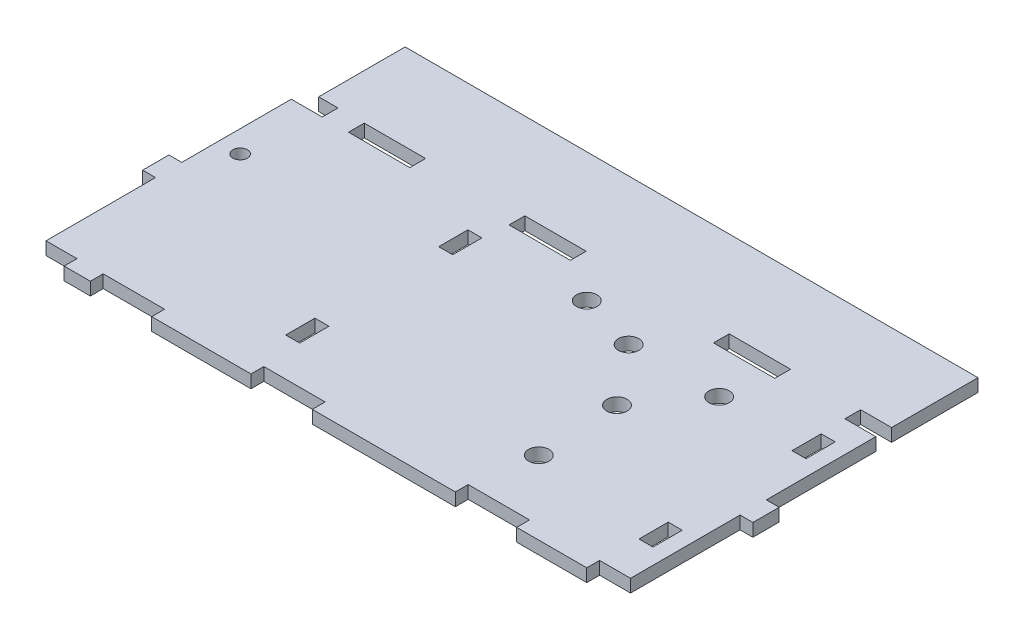
SolidWorks part; units mm, degrees
ref_plane "Front Plane" through (0, 0, 0) normal (0, 0, 1) x (1, 0, 0)
ref_plane "Top Plane" through (0, 0, 0) normal (0, 1, 0) x (1, 0, 0)
ref_plane "Right Plane" through (0, 0, 0) normal (1, 0, 0) x (0, 0, -1)
sketch "Sketch1" plane through (0, 0, 0) normal (0, 1, 0) x (1, 0, 0)
  line L0 (-110.6901, 12.3801) -> (-116.2781, 12.3801)
  line L2 (-110.6901, -46.6749) -> (-110.6901, 0.9501)
  line L4 (143.5639, -46.6749) -> (143.5639, 0.9501)
  line L5 (-110.6901, -46.6749) -> (143.5639, 60.0051) construction
  line L6 (-110.6901, 60.0051) -> (143.5639, -46.6749) construction
  line L7 (-116.2781, 12.3801) -> (-116.2781, 0.9501)
  line L8 (-116.2781, 0.9501) -> (-110.6901, 0.9501)
  line L9 (-110.6901, 12.3801) -> (-110.6901, 60.0051)
  line L10 (10.7219, 63.4341) -> (72.9519, 63.4341) construction
  line L11 (149.1519, 0.9501) -> (143.5639, 0.9501)
  line L12 (149.1519, 12.3801) -> (149.1519, 0.9501)
  line L13 (143.5639, 12.3801) -> (149.1519, 12.3801)
  line L14 (143.5639, 12.3801) -> (143.5639, 60.0051)
  line L23 (-108.712, 0) -> (106.818, 0) construction
  line L32 (-110.6901, 60.0051) -> (-97.2281, 60.0051)
  line L33 (-110.6901, -46.6749) -> (-97.2281, -46.6749)
  line L34 (-85.7981, 60.0051) -> (-59.1281, 60.0051)
  line L36 (-97.2281, 60.0051) -> (-97.2281, 66.8631)
  line L38 (-85.7981, 60.0051) -> (-85.7981, 66.8631)
  line L40 (-59.1281, 60.0051) -> (-59.1281, 66.8631)
  line L42 (-15.9481, 60.0051) -> (-15.9481, 66.8631)
  line L44 (10.7219, 60.0051) -> (10.7219, 66.8631)
  line L46 (72.9519, 60.0051) -> (72.9519, 66.8631)
  line L48 (99.6219, 60.0051) -> (99.6219, 66.8631)
  line L50 (130.1019, 60.0051) -> (130.1019, 66.8631)
  line L51 (-15.9481, 60.0051) -> (10.7219, 60.0051)
  line L52 (72.9519, 60.0051) -> (99.6219, 60.0051)
  line L53 (130.1019, 60.0051) -> (143.5639, 60.0051)
  line L54 (130.1019, -46.6749) -> (130.1019, -52.2629)
  line L55 (99.6219, -52.2629) -> (130.1019, -52.2629)
  line L56 (99.6219, -46.6749) -> (99.6219, -52.2629)
  line L57 (72.9519, -46.6749) -> (72.9519, -52.2629)
  line L58 (10.7219, -52.2629) -> (72.9519, -52.2629)
  line L59 (10.7219, -46.6749) -> (10.7219, -52.2629)
  line L60 (-15.9481, -46.6749) -> (-15.9481, -52.2629)
  line L61 (-59.1281, -52.2629) -> (-15.9481, -52.2629)
  line L62 (-59.1281, -46.6749) -> (-59.1281, -52.2629)
  line L63 (-85.7981, -46.6749) -> (-85.7981, -52.2629)
  line L64 (-97.2281, -52.2629) -> (-85.7981, -52.2629)
  line L65 (-97.2281, -46.6749) -> (-97.2281, -52.2629)
  line L66 (-85.7981, -46.6749) -> (-59.1281, -46.6749)
  line L67 (-15.9481, -46.6749) -> (10.7219, -46.6749)
  line L68 (72.9519, -46.6749) -> (99.6219, -46.6749)
  line L69 (130.1019, -46.6749) -> (143.5639, -46.6749)
  line L70 (130.1019, 66.8631) -> (143.5639, 66.8631)
  line L71 (143.5639, 66.8631) -> (143.5639, 104.4551)
  line L72 (-97.2281, 66.8631) -> (-105.6101, 66.8631)
  line L73 (-105.6101, 66.8631) -> (-105.6101, 104.4551)
  line L74 (-105.6101, 104.4551) -> (143.5639, 104.4551)
  line L75 (99.6219, 66.8631) -> (72.9519, 66.8631)
  line L76 (10.7219, 66.8631) -> (-15.9481, 66.8631)
  line L77 (-59.1281, 66.8631) -> (-85.7981, 66.8631)
  line L78 (-97.2281, 63.4341) -> (-85.7981, 63.4341) construction
  line L79 (-91.5131, 63.4341) -> (-91.5131, -53.3153) construction
  line L80 (-59.1281, 63.4341) -> (-15.9481, 63.4341) construction
  line L81 (-37.5381, 63.4341) -> (-37.5381, -52.2629) construction
  line L82 (41.8369, 63.4341) -> (41.8369, -52.2629) construction
  line L83 (99.6219, 63.4341) -> (130.1019, 63.4341) construction
  line L84 (114.8619, 63.4341) -> (114.8619, -52.2629) construction
  point P0 (0, 0)
  point P57 (-91.5131, -52.2629)
  point P63 (-37.5381, -52.2629)
  point P66 (41.8369, -52.2629)
  dimension "D1" = 106.68
  dimension "D3" = 11.43
  dimension "D4" = 5.588
  dimension "D5" = 6.858
  dimension "D6" = 11.43
  dimension "D7" = 26.67
  dimension "D8" = 13.462
  dimension "D10" = 106.68
  dimension "D11" = 11.43
  dimension "D12" = 6.858
  dimension "D13" = 37.592
  dimension "D14" = 5.588
  dimension "D15" = 5.588
  dimension "D16" = 47.625
  dimension "D17" = 47.625
  dimension "D18" = 47.625
  dimension "D19" = 47.625
  dimension "D20" = 62.23
  dimension "D21" = 11.43
  dimension "D23" = 43.18
  dimension "D26" = 26.67
  dimension "D27" = 30.48
  dimension "D28" = 13.462
  dimension "D29" = 110.6901
  dimension "D30" = 26.67
  dimension "D31" = 43.18
  dimension "D32" = 62.23
  dimension "D33" = 26.67
  dimension "D34" = 30.48
  dimension "D35" = 8.382
extrude "Boss-Extrude1" add sketch "Sketch1" along normal blind 5.588
sketch "Sketch9" plane through (0, 5.588, 0) normal (0, 1, 0) x (1, 0, 0)
  line L0 (-110.6901, 0.9501) -> (-110.6901, -46.6749) construction
  line L1 (-23.0601, -17.3379) -> (-16.9641, -17.3379)
  line L2 (-23.0601, -17.3379) -> (-23.0601, -30.0379)
  line L3 (-23.0601, -30.0379) -> (-16.9641, -30.0379)
  line L4 (-16.9641, -17.3379) -> (-16.9641, -30.0379)
  line L5 (-85.7981, -46.6749) -> (-59.1281, -46.6749) construction
  line L6 (-23.0601, 36.5101) -> (-16.9641, 36.5101)
  line L7 (-23.0601, 36.5101) -> (-23.0601, 49.2101)
  line L8 (-23.0601, 49.2101) -> (-16.9641, 49.2101)
  line L9 (-16.9641, 36.5101) -> (-16.9641, 49.2101)
  line L10 (130.6099, -17.3379) -> (136.7059, -17.3379)
  line L11 (130.6099, -17.3379) -> (130.6099, -30.0379)
  line L12 (130.6099, -30.0379) -> (136.7059, -30.0379)
  line L13 (136.7059, -17.3379) -> (136.7059, -30.0379)
  line L14 (130.6099, 49.2101) -> (136.7059, 49.2101)
  line L15 (130.6099, 49.2101) -> (130.6099, 36.5101)
  line L16 (130.6099, 36.5101) -> (136.7059, 36.5101)
  line L17 (136.7059, 49.2101) -> (136.7059, 36.5101)
  line L18 (143.5639, -46.6749) -> (143.5639, 0.9501) construction
  line L19 (143.5639, 12.3801) -> (143.5639, 60.0051) construction
  dimension "D1" = 12.7
  dimension "D2" = 6.096
  dimension "D3" = 87.63
  dimension "D4" = 16.637
  dimension "D5" = 87.63
  dimension "D6" = 83.185
  dimension "D7" = 12.7
  dimension "D8" = 6.096
  dimension "D9" = 12.7
  dimension "D10" = 6.096
  dimension "D11" = 6.096
  dimension "D12" = 12.7
  dimension "D13" = 6.858
  dimension "D14" = 6.858
extrude "Cut-Extrude1" cut sketch "Sketch9" against normal up to next
sketch "Sketch12" plane through (0, 5.588, 0) normal (0, 1, 0) x (1, 0, 0)
  line L0 (-97.2281, 60.0051) -> (-110.6901, 60.0051) construction
  line L1 (-110.6901, 60.0051) -> (-110.6901, 12.3801) construction
  circle A0 centre (-101.1651, 28.2551) radius 3.175
  point P4 (-103.9591, 60.0051)
  dimension "D1" = 6.35
  dimension "D2" = 31.75
  dimension "D3" = 9.525
extrude "Cut-Extrude2" cut sketch "Sketch12" against normal up to next
sketch "Sketch13" plane through (0, 0, 0) normal (0, -1, 0) x (1, 0, 0)
  line L0 (72.9519, -60.0051) -> (99.6219, -60.0051) construction
  line L1 (80.3219, 21.1079) -> (80.3219, 31.4079) construction
  line L2 (28.6689, -45.3198) -> (18.3689, -45.3198) construction
  line L3 (12.9689, -23.6698) -> (12.9689, -44.4698) construction
  line L4 (79.4719, 36.8079) -> (58.6719, 36.8079) construction
  circle A0 centre (77.2739, 20.2979) radius 4.445
  circle A2 centre (55.0998, -40.9551) radius 4.445
  circle A3 centre (94.4744, -40.9551) radius 4.445
  circle A4 centre (75.4244, -15.5551) radius 4.445
  circle A5 centre (29.4789, -48.3678) radius 4.445
  point P34 (23.5189, -45.3198)
  dimension "D1" = 19.05
  dimension "D2" = 3.048
  dimension "D3" = 8.89
  dimension "D4" = 3.048
  dimension "D5" = 16.51
  dimension "D6" = 16.51
  dimension "D8" = 19.05
extrude "Cut-Extrude3" cut sketch "Sketch13" against normal up to next
sketch "Sketch14" plane through (0, 5.588, 0) normal (0, 1, 0) x (1, 0, 0)
  line L0 (143.5639, -46.6749) -> (143.5639, 0.9501) construction
  line L1 (137.2139, 0.9501) -> (140.3889, 0.9501)
  line L2 (137.2139, 0.9501) -> (137.2139, 13.6501)
  line L3 (137.2139, 13.6501) -> (140.3889, 13.6501)
  line L4 (140.3889, 0.9501) -> (140.3889, 13.6501)
  line L5 (143.5639, 0.9501) -> (149.1519, 0.9501) construction
  dimension "D1" = 3.175
  dimension "D2" = 12.7
  dimension "D3" = 3.175
